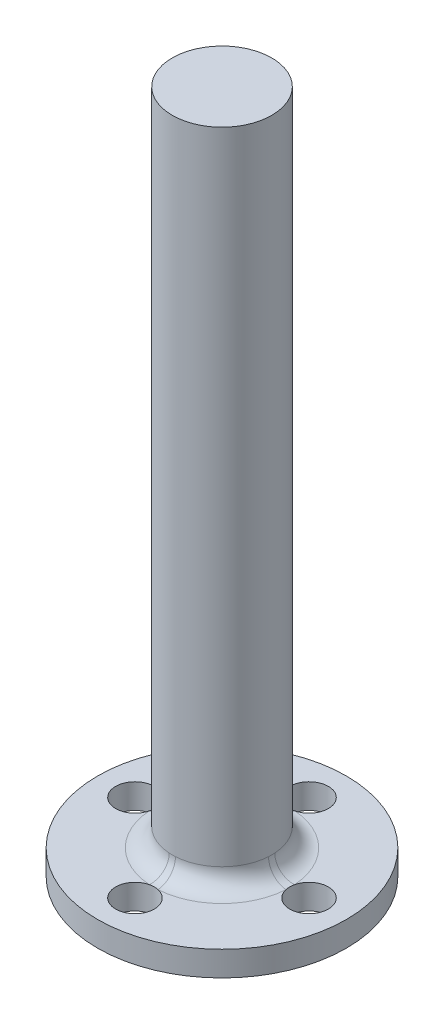
SolidWorks part; units mm, degrees
ref_plane "前视基准面" through (0, 0, 0) normal (0, 0, 1) x (1, 0, 0)
ref_plane "上视基准面" through (0, 0, 0) normal (0, 1, 0) x (1, 0, 0)
ref_plane "右视基准面" through (0, 0, 0) normal (1, 0, 0) x (0, 0, -1)
other "Configuration Table"
sketch "草图1" plane through (0, 0, 0) normal (0, 1, 0) x (1, 0, 0)
  circle A0 centre (0, 0) radius 10
  dimension "D1" = 20
extrude "凸台-拉伸1" add sketch "草图1" along normal blind 2
sketch "草图2" plane through (0, 2, 0) normal (0, 1, 0) x (1, 0, 0)
  circle A0 centre (0, 0) radius 7 construction
  circle A1 centre (0, 7) radius 1.55
  circle A2 centre (7, 0) radius 1.55
  circle A3 centre (-7, 0) radius 1.55
  circle A4 centre (0, -7) radius 1.55
  dimension "D1" = 14
  dimension "D2" = 3.1
extrude "切除-拉伸1" cut sketch "草图2" against normal blind 2
sketch "草图3" plane through (0, 2, 0) normal (0, 1, 0) x (1, 0, 0)
  circle A0 centre (0, 0) radius 4
  dimension "D1" = 8
extrude "凸台-拉伸2" add sketch "草图3" along normal blind 53
fillet "圆角1" radius 1.5 1 edges at (0, 2, 4)
